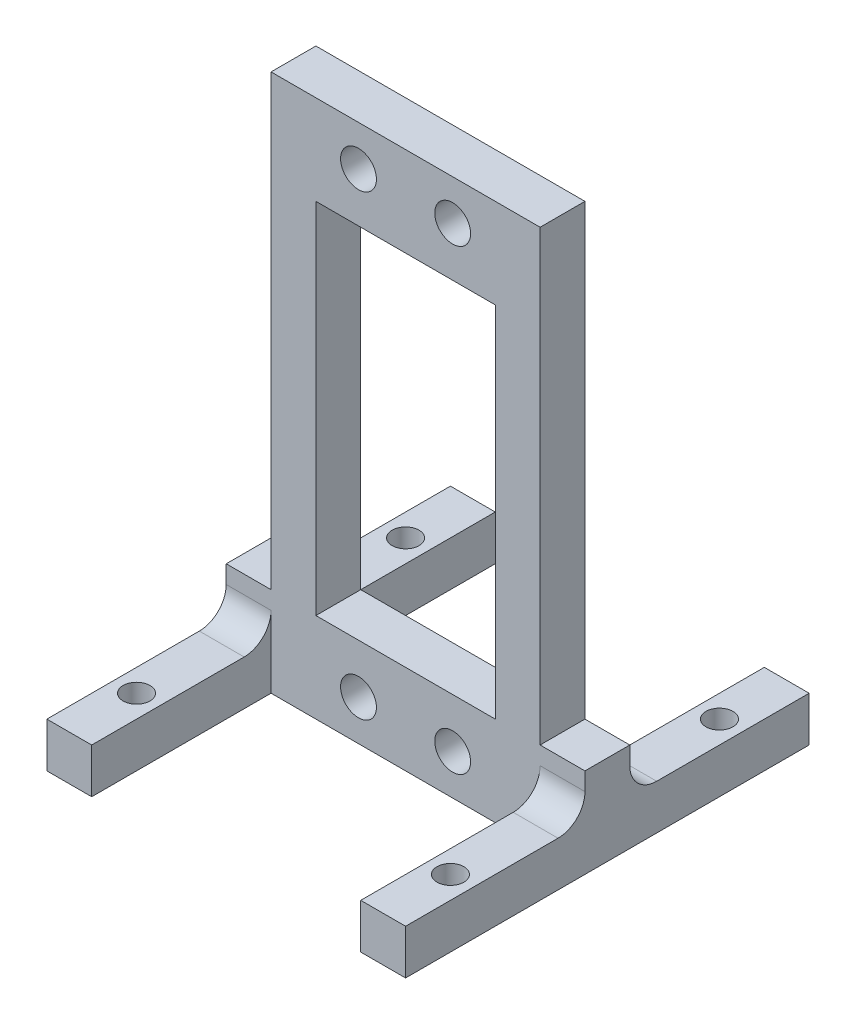
SolidWorks part; units mm, degrees
ref_plane "Front" through (0, 0, 0) normal (0, 0, 1) x (1, 0, 0)
ref_plane "Top" through (0, 0, 0) normal (0, 1, 0) x (1, 0, 0)
ref_plane "Right" through (0, 0, 0) normal (1, 0, 0) x (0, 0, -1)
sketch "草图2" plane through (0, 0, 0) normal (0, 0, 1) x (1, 0, 0)
  line L0 (10, 0) -> (10, 10) construction
  line L1 (0, 0) -> (20, 0)
  line L2 (0, 0) -> (0, -40)
  line L3 (0, -40) -> (20, -40)
  line L4 (20, 0) -> (20, -40)
  line L6 (10, 10) -> (25, 10) construction
  line L7 (10, -50) -> (25, -50) construction
  line L8 (25, -50) -> (-5, -50)
  line L9 (25, 10) -> (25, -50)
  line L10 (-5, -50) -> (-5, 10)
  line L11 (-5, 10) -> (25, 10)
  dimension "D1" = 20
  dimension "D2" = 40
extrude "凸台-拉伸1" add sketch "草图2" along normal blind 5
sketch "草图3" plane through (0, 0, 5) normal (0, 0, 1) x (1, 0, 0)
  line L4 (15.25, 3.5) -> (15.25, 5.5)
  line L5 (15.25, -43.5) -> (15.25, -45.5)
  line L6 (4.75, 3.5) -> (4.75, 5.5)
  line L7 (4.75, -43.5) -> (4.75, -45.5)
  circle A0 centre (15.25, 5.5) radius 2
  circle A1 centre (15.25, -45.5) radius 2
  circle A2 centre (4.75, -45.5) radius 2
  circle A3 centre (4.75, 5.5) radius 2
extrude "切除-拉伸1" cut sketch "草图3" against normal blind 5
sketch "草图5" plane through (25, 0, 0) normal (1, 0, 0) x (0, 0, -1)
  line L0 (-5, -42) -> (-5, -40)
  line L1 (-5, -50) -> (-5, 10) construction
  line L3 (-5, -50) -> (0, -50)
  line L4 (-5, -50) -> (0, -50) construction
  line L5 (0, -42) -> (0, -40)
  line L8 (-5, -40) -> (0, -40)
  line L9 (0, -50) -> (20, -50)
  line L10 (3, -45) -> (20, -45)
  line L11 (20, -45) -> (20, -50)
  line L13 (-5, -50) -> (-25, -50)
  line L14 (-25, -45) -> (-25, -50)
  line L15 (-8, -45) -> (-25, -45)
  arc A2 (3, -45) -> (0, -42) centre (3, -42) cw
  arc A3 (-5, -42) -> (-8, -45) centre (-8, -42) cw
  point P13 (-5, -40)
  dimension "D1" = 3
ref_plane "基准面1" through (10, 0, 0) normal (1, 0, 0) x (0, 0, -1)
extrude "凸台-拉伸2" add sketch "草图5" along normal blind 5
mirror "镜向1" about plane through (10, 0, 0) normal (1, 0, 0) of "凸台-拉伸2"
sketch "草图6" plane through (0, -45, 0) normal (0, 1, 0) x (1, 0, 0)
  line L0 (30, -2.5) -> (-10, -2.5) construction
  line L1 (30, 0) -> (30, -5) construction
  line L2 (-10, 0) -> (-10, -5) construction
  line L3 (-10, -17.5) -> (-10, 12.5) construction
  line L4 (-10, 20) -> (-10, 3) construction
  line L5 (10, -2.5) -> (10, -23.8536) construction
  line L6 (10, -50) -> (10, 50) construction
  line L7 (30, -17.5) -> (30, 12.5) construction
  line L8 (-10, 12.5) -> (-7.5, 12.5)
  circle A0 centre (-7.5, 12.5) radius 1.5
  circle A1 centre (-7.5, -17.5) radius 1.5
  circle A2 centre (27.5, -17.5) radius 1.5
  circle A3 centre (27.5, 12.5) radius 1.5
  point P24 (0, 0)
extrude "切除-拉伸2" cut sketch "草图6" against normal blind 5
